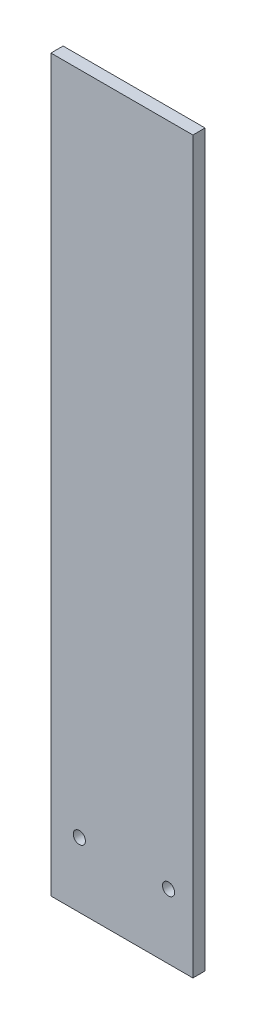
SolidWorks part; units mm, degrees
material "MDF"
ref_plane "Alzado" through (0, 0, 0) normal (0, 0, 1) x (1, 0, 0)
ref_plane "Planta" through (0, 0, 0) normal (0, 1, 0) x (1, 0, 0)
ref_plane "Vista lateral" through (0, 0, 0) normal (1, 0, 0) x (0, 0, -1)
sketch "Croquis2" plane through (0, 0, 0) normal (0, 0, 1) x (1, 0, 0)
  line L1 (-17.5, 90) -> (17.5, 90)
  line L2 (-17.5, 90) -> (-17.5, -90)
  line L3 (-17.5, -90) -> (17.5, -90)
  line L4 (17.5, 90) -> (17.5, -90)
  line L5 (-17.5, 90) -> (17.5, -90) construction
  line L6 (-17.5, -90) -> (17.5, 90) construction
  circle A0 centre (11.5, -74) radius 1.5
  circle A1 centre (-10.5, -74) radius 1.5
  point P0 (0, 0)
  dimension "D3" = 3
  dimension "D1" = 180
  dimension "D2" = 35
  dimension "D4" = 16
  dimension "D5" = 6
  dimension "D6" = 22
extrude "Saliente-Extruir1" add sketch "Croquis2" along normal blind 3
